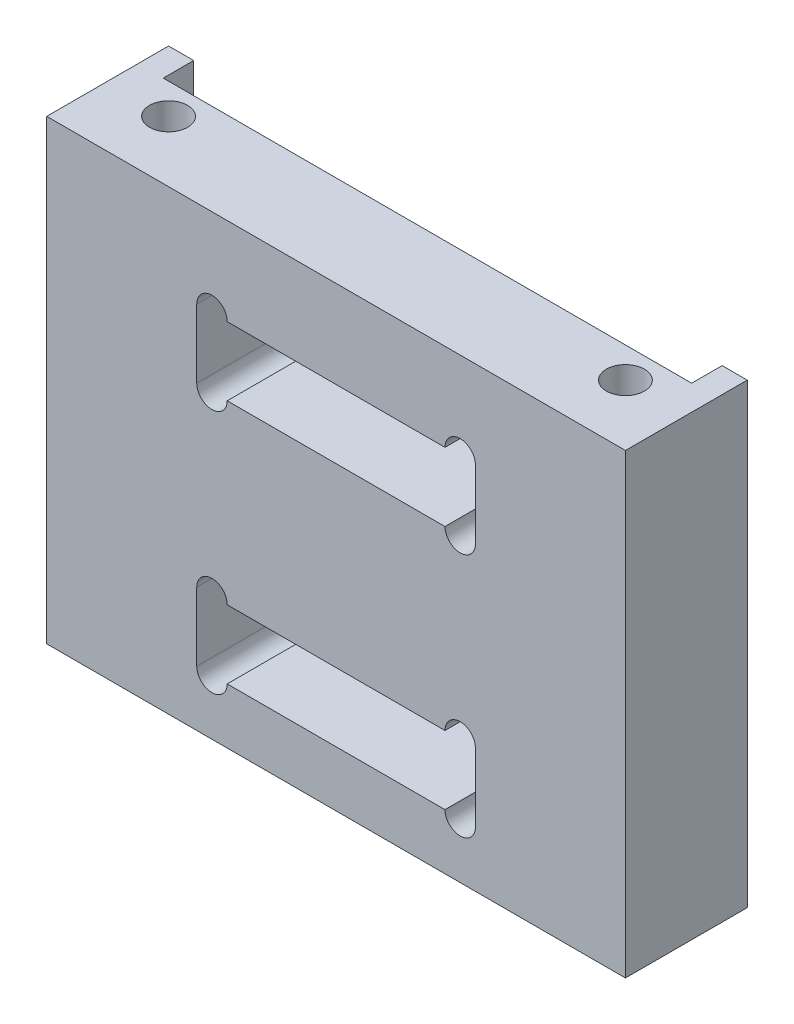
SolidWorks part; units mm, degrees
material "1.0503 (C45)"
ref_plane "Front Plane" through (0, 0, 0) normal (0, 0, 1) x (1, 0, 0)
ref_plane "Top Plane" through (0, 0, 0) normal (0, 1, 0) x (1, 0, 0)
ref_plane "Right Plane" through (0, 0, 0) normal (1, 0, 0) x (0, 0, -1)
sketch "Sketch1" plane through (0, 0, 0) normal (0, 0, 1) x (1, 0, 0)
  line L1 (19, -15) -> (-19, -15)
  line L2 (19, -15) -> (19, 15)
  line L3 (19, 15) -> (-19, 15)
  line L4 (-19, -15) -> (-19, 15)
  line L5 (19, -15) -> (-19, 15) construction
  line L6 (19, 15) -> (-19, -15) construction
  point P0 (0, 0)
  dimension "D1" = 30
  dimension "D2" = 38
extrude "Boss-Extrude1" add sketch "Sketch1" along normal mid plane 8
sketch "Sketch2" plane through (0, 0, -4) normal (0, 0, 1) x (1, 0, 0)
  line L0 (-11.65, -13.2) -> (-11.65, -15) construction
  line L1 (-19, -15) -> (19, -15) construction
  line L2 (-11.65, -15) -> (11.65, -15) construction
  line L3 (11.65, -15) -> (11.65, -13.2) construction
  line L4 (-11.65, -13.2) -> (-17.35, -13.2) construction
  line L5 (-17.35, -13.2) -> (-17.35, -3.15)
  line L6 (11.65, -13.2) -> (17.35, -13.2) construction
  line L7 (17.35, -13.2) -> (17.35, -3.15)
  line L8 (-15.85, -1.65) -> (15.85, -1.65) construction
  line L9 (0, -55) -> (0, 55) construction
  line L10 (-15.85, 17) -> (15.85, 17)
  line L11 (17.35, 15.5) -> (17.35, -1.5)
  line L12 (15.85, -3) -> (-15.85, -3) construction
  line L13 (-17.35, -1.5) -> (-17.35, 15.5)
  line L14 (-15.85, 15.5) -> (15.85, -1.5) construction
  line L15 (-15.85, -1.5) -> (15.85, 15.5) construction
  line L16 (17.35, -13.2) -> (17.35, -15)
  line L17 (-19, -15) -> (19, -15) construction
  line L18 (17.35, -15) -> (-17.35, -15)
  line L19 (-17.35, -15) -> (-17.35, -13.2)
  line L20 (17.35, -1.5) -> (17.35, -3.15)
  line L21 (-17.35, -1.5) -> (-17.35, -3.15)
  arc A0 (-17.35, -3.15) -> (-15.85, -1.65) centre (-15.85, -3.15) cw construction
  arc A1 (17.35, -3.15) -> (15.85, -1.65) centre (15.85, -3.15) ccw construction
  arc A2 (15.85, 17) -> (17.35, 15.5) centre (15.85, 15.5) cw
  arc A3 (17.35, -1.5) -> (15.85, -3) centre (15.85, -1.5) cw construction
  arc A4 (-15.85, -3) -> (-17.35, -1.5) centre (-15.85, -1.5) cw construction
  arc A5 (-17.35, 15.5) -> (-15.85, 17) centre (-15.85, 15.5) cw
  point P14 (0, -1.65)
  point P17 (0, -15)
  point P21 (0, 17)
  point P33 (0, 7)
  dimension "D3" = 1.5
  dimension "D6" = 1.5
  dimension "D1" = 34.7
  dimension "D2" = 13.35
  dimension "D4" = 1.8
  dimension "D5" = 23.3
  dimension "D7" = 20
  dimension "D8" = 34.7
  dimension "D9" = 22
extrude "Cut-Extrude1" cut sketch "Sketch2" along normal blind 2
sketch "Sketch3" plane through (0, 0, -2) normal (0, 0, -1) x (-1, 0, 0)
  line L0 (17.35, -15) -> (-17.35, -15) construction
  line L1 (-7.15, -11.35) -> (7.15, -11.35) construction
  line L2 (-9.15, -11.35) -> (-9.15, -6.85) construction
  line L3 (-7.15, -6.85) -> (7.15, -6.85) construction
  line L4 (9.15, -11.35) -> (9.15, -6.85) construction
  line L5 (0, -9.1) -> (9.15, -6.85) construction
  line L6 (0, -9.1) -> (9.15, -11.35) construction
  line L7 (-7.15, 4.75) -> (7.15, 4.75) construction
  line L8 (-9.15, 4.75) -> (-9.15, 9.25) construction
  line L9 (-7.15, 9.25) -> (7.15, 9.25) construction
  line L10 (9.15, 4.75) -> (9.15, 9.25) construction
  line L11 (0, 7) -> (9.15, 9.25) construction
  line L12 (0, 7) -> (9.15, 4.75) construction
  line L13 (0, 55) -> (0, -55) construction
  line L14 (9.15, 9.25) -> (9.15, 4.75)
  line L15 (7.15, 4.75) -> (-7.15, 4.75)
  line L16 (-9.15, 4.75) -> (-9.15, 9.25)
  line L17 (-7.15, 9.25) -> (7.15, 9.25)
  line L18 (-7.15, -6.85) -> (7.15, -6.85)
  line L19 (9.15, -6.85) -> (9.15, -11.35)
  line L20 (7.15, -11.35) -> (-7.15, -11.35)
  line L21 (-9.15, -11.35) -> (-9.15, -6.85)
  line L22 (-9.15, 9.25) -> (-7.15, 9.25) construction
  line L23 (-9.15, 4.75) -> (-7.15, 4.75) construction
  line L24 (7.15, 4.75) -> (9.15, 4.75) construction
  line L25 (7.15, 9.25) -> (9.15, 9.25) construction
  line L26 (-9.15, -11.35) -> (-7.15, -11.35) construction
  line L27 (-9.15, -11.35) -> (0, -9.1) construction
  line L28 (7.15, -6.85) -> (9.15, -6.85) construction
  line L29 (7.15, -11.35) -> (9.15, -11.35) construction
  line L30 (-9.15, -11.35) -> (-7.15, -11.35) construction
  line L31 (-9.15, -6.85) -> (-7.15, -6.85) construction
  line L32 (-9.15, 9.25) -> (-7.15, 9.25) construction
  line L33 (-9.15, 9.25) -> (0, 7) construction
  line L34 (-9.15, 4.75) -> (0, 7) construction
  line L35 (-9.15, 4.75) -> (-7.15, 4.75) construction
  line L36 (7.15, 9.25) -> (9.15, 9.25) construction
  line L37 (7.15, 4.75) -> (9.15, 4.75) construction
  line L38 (-9.15, -6.85) -> (-7.15, -6.85) construction
  line L39 (-9.15, -6.85) -> (0, -9.1) construction
  line L40 (7.15, -6.85) -> (9.15, -6.85) construction
  line L41 (7.15, -11.35) -> (9.15, -11.35) construction
  arc A0 (-9.15, 4.75) -> (-7.15, 4.75) centre (-8.15, 4.75) ccw
  arc A1 (9.15, 4.75) -> (7.15, 4.75) centre (8.15, 4.75) cw
  arc A2 (-9.15, 9.25) -> (-7.15, 9.25) centre (-8.15, 9.25) cw
  arc A3 (9.15, 9.25) -> (7.15, 9.25) centre (8.15, 9.25) ccw
  arc A4 (-9.15, -6.85) -> (-7.15, -6.85) centre (-8.15, -6.85) cw
  arc A5 (-9.15, -11.35) -> (-7.15, -11.35) centre (-8.15, -11.35) ccw
  arc A6 (9.15, -11.35) -> (7.15, -11.35) centre (8.15, -11.35) cw
  arc A7 (9.15, -6.85) -> (7.15, -6.85) centre (8.15, -6.85) ccw
  point P0 (0, -9.1)
  point P5 (0, 7)
  dimension "D1" = 22
  dimension "D2" = 4.5
  dimension "D3" = 5.9
  dimension "D4" = 18.3
  dimension "D5" = 2
  dimension "D6" = 2
extrude "Cut-Extrude2" cut sketch "Sketch3" against normal through all
hole_wizard "M3 Tapped Hole1" positions "Sketch4" profile "Sketch5" tap size "M3" standard "ISO"
sketch "Sketch4" plane through (0, -15, 0) normal (0, -1, 0) x (-1, 0, 0)
  line L0 (0, 55) -> (0, -55) construction
  line L1 (-55, 0) -> (55, 0) construction
  point P0 (-14.5, 0)
  dimension "D1" = 14.5
sketch "Sketch5" plane through (14.5, -15, 0) normal (1, 0, 0) x (0, 0, -1)
  line L0 (0, 0) -> (0, 6.7511)
  line L1 (0, 6.7511) -> (1.25, 6)
  line L2 (1.25, 6) -> (1.25, 0)
  line L5 (1.25, 0) -> (0, 0)
  line L10 (0, 6.7511) -> (-1.25, 6) construction
  line L11 (0, -6.35) -> (0, 107.95) construction
  dimension "Tap Drill Dia." = 2.5
  dimension "Tap Drill Depth" = 6
  dimension "Drill Angle" = 118
cosmetic thread "Cosmetic Thread1" parameters "D2"=3
fillet "Fillet1" [suppressed] radius 1.05
sketch "Sketch6" plane through (-19, 0, 0) normal (-1, 0, 0) x (0, 0, 1)
  line L0 (-4, 15) -> (-4, -15) construction
  line L1 (-4, 12.45) -> (4, 12.45)
  line L2 (-4, 12.45) -> (-4, 8.95)
  line L3 (-4, 8.95) -> (4, 8.95)
  line L4 (4, 12.45) -> (4, 8.95)
  line L5 (4, 15) -> (4, -15) construction
  line L6 (4, -15) -> (-4, -15) construction
  line L7 (-4, -4.5) -> (4, -4.5)
  line L8 (-4, -4.5) -> (-4, -8)
  line L9 (-4, -8) -> (4, -8)
  line L10 (4, -4.5) -> (4, -8)
  point P8 (0, 0)
  dimension "D1" = 3.5
  dimension "D2" = 7
  dimension "D3" = 23.95
extrude "Cut-Extrude3" [suppressed] cut sketch "Sketch6" against normal blind 3.5
mirror "Mirror1" about plane through (0, 0, 0) normal (1, 0, 0) of "Cut-Extrude3", "M3 Tapped Hole1"
cosmetic thread "Cosmetic Thread2" parameters "D2"=3
fillet "Fillet2" [suppressed] radius 1
hole_wizard "Tap Drill for M3 Tap1" positions "Sketch7" profile "Sketch8" hole size "M3" standard "ISO"
sketch "Sketch7" plane through (0, 15, 0) normal (0, 1, 0) x (1, 0, 0)
  line L0 (0, -55) -> (0, 55) construction
  line L1 (-55, 0) -> (55, 0) construction
  point P0 (15, 0)
  point P2 (-15, 0)
  dimension "D1" = 15
  dimension "D2" = 15
sketch "Sketch8" plane through (15, 15, 0) normal (1, 0, 0) x (0, 0, 1)
  line L0 (0, 0) -> (0, 5.7511)
  line L1 (0, 5.7511) -> (1.25, 5)
  line L2 (1.25, 5) -> (1.25, 0)
  line L5 (1.25, 0) -> (0, 0)
  line L10 (0, 5.7511) -> (-1.25, 5) construction
  line L11 (0, -6.35) -> (0, 107.95) construction
  dimension "Hole Dia." = 2.5
  dimension "Hole Depth" = 5
  dimension "Drill Angle" = 118
cosmetic thread "Cosmetic Thread3" parameters "D2"=3
cosmetic thread "Cosmetic Thread4" parameters "D2"=3
sketch "Sketch9" [suppressed] plane through (0, 0, 4) normal (0, 0, 1) x (1, 0, 0)
  line L0 (19, -16) -> (14.5, -16)
  line L1 (-19, -16) -> (-14.5, -16)
  line L2 (-19, -16) -> (19, -16) construction
  line L3 (14.5, -16) -> (14.5, -9)
  line L4 (12, -10.5) -> (17, -10.5)
  line L5 (12, -10.5) -> (12, -7.5)
  line L6 (12, -7.5) -> (17, -7.5)
  line L7 (17, -10.5) -> (17, -7.5)
  line L8 (12, -10.5) -> (17, -7.5) construction
  line L9 (12, -7.5) -> (17, -10.5) construction
  line L10 (-14.5, -16) -> (-14.5, -9)
  line L12 (-17, -10.5) -> (-12, -10.5)
  line L13 (-17, -10.5) -> (-17, -7.5)
  line L14 (-17, -7.5) -> (-12, -7.5)
  line L15 (-12, -10.5) -> (-12, -7.5)
  line L16 (-17, -10.5) -> (-12, -7.5) construction
  line L17 (-17, -7.5) -> (-12, -10.5) construction
  dimension "D1" = 3
  dimension "D2" = 5
  dimension "D3" = 3
  dimension "D4" = 5
equation "\"Radius\"=1.5"
equation "\"D6@Sketch2\"=\"Radius\""
equation "\"D3@Sketch2\"=\"Radius\""
equation "\"Height_core\"= 14.9"
equation "\"D2@Sketch2\" = \"Height_core\" - 1.55"
equation "\"Width_core\"= 34.4 + 0.3"
equation "\"D8@Sketch2\" = \"Width_core\""
equation "\"D1@Sketch2\" = \"Width_core\""
equation "\"Width_Holder\"= 38"
equation "\"D2@Sketch1\"=\"Width_Holder\""
equation "\"Height_Holder\"=30"
equation "\"D1@Sketch1\"=\"Height_Holder\""
equation "\"Height_Kicker\"= 22"
equation "\"D9@Sketch2\"=\"Height_Kicker\""
equation "\"D1@Sketch3\"=\"Height_Kicker\""
equation "\"Height_core_hole\"=4.5"
equation "\"D2@Sketch3\"=\"Height_core_hole\""
equation "\"D3@Sketch3\"=\"Height_core\"/2-1.55"
equation "\"Width_core_hole\"=18.3"
equation "\"D4@Sketch3\"=\"Width_core_hole\""
equation "\"D6@Sketch3\"=\"D5@Sketch3\""
equation "\"D1@Sketch4\" = \"Width_Holder\" / 2 - 4.5"
equation "\"D2@Sketch7\"=\"D1@Sketch7\""
